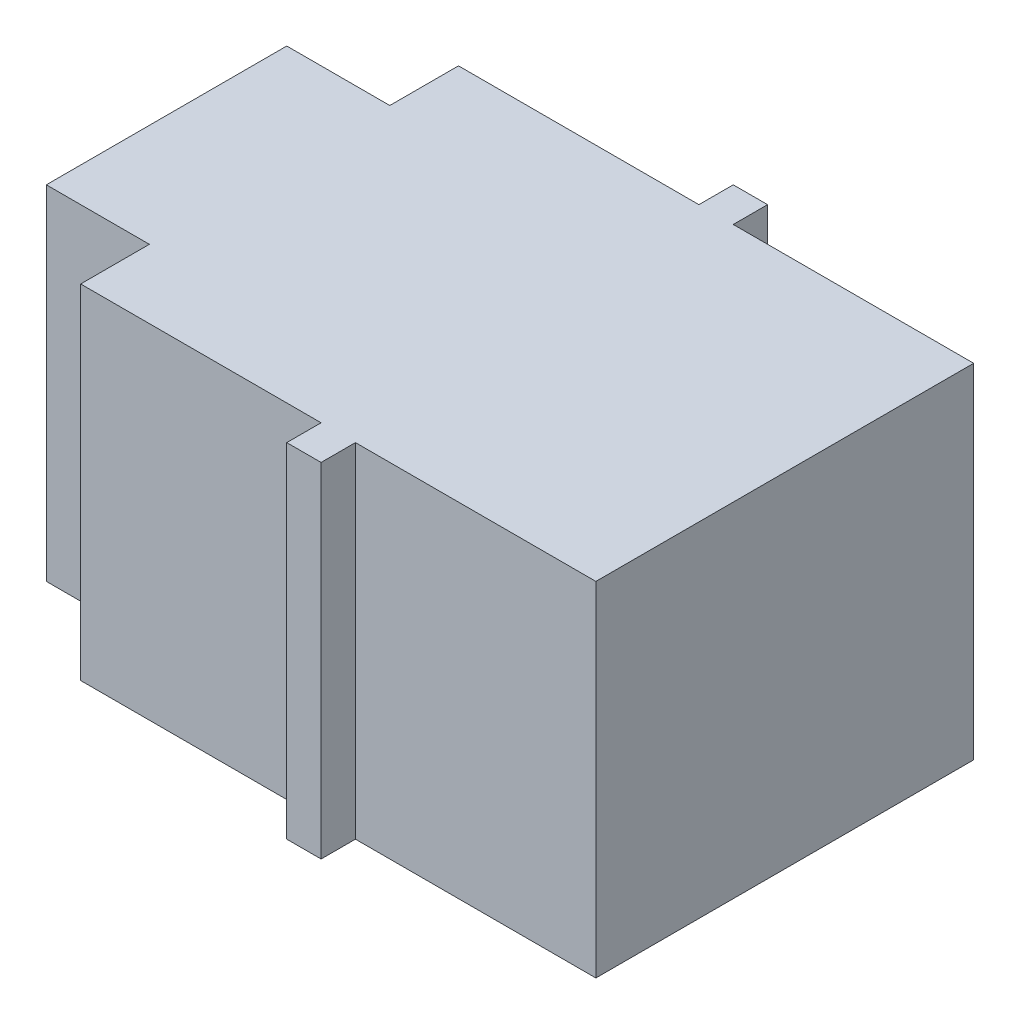
SolidWorks part; units mm, degrees
ref_plane "Front Plane" through (0, 0, 0) normal (0, 0, 1) x (1, 0, 0)
ref_plane "Top Plane" through (0, 0, 0) normal (0, 1, 0) x (1, 0, 0)
ref_plane "Right Plane" through (0, 0, 0) normal (1, 0, 0) x (0, 0, -1)
sketch "Sketch1" plane through (0, 0, 0) normal (0, 1, 0) x (1, 0, 0)
  line L0 (7.9713, 0) -> (-10.0287, 0) construction
  line L1 (-10.0287, -3.5) -> (-10.0287, 3.5)
  line L2 (-9.8287, 3.3) -> (-6.8287, 3.3)
  line L3 (-9.8287, -3.3) -> (-9.8287, 2.3) construction
  line L4 (-10.0287, -3.5) -> (-10.0287, 2.5) construction
  line L5 (-10.0287, 3.5) -> (-7.0287, 3.5)
  line L6 (-6.8287, 3.3) -> (-6.8287, 5.3)
  line L7 (-6.8287, 5.3) -> (0.1713, 5.3)
  line L8 (0.1713, 5.3) -> (0.7713, 5.3)
  line L9 (7.9713, 5.5) -> (7.9713, -5.5)
  line L10 (0.9713, -5.5) -> (7.9713, -5.5)
  line L11 (0.9713, -6.5) -> (0.9713, -5.5)
  line L12 (-0.0287, -6.5) -> (0.9713, -6.5)
  line L13 (-0.0287, -5.5) -> (-0.0287, -6.5)
  line L14 (-7.0287, -5.5) -> (-0.0287, -5.5)
  line L15 (-7.0287, -3.5) -> (-7.0287, -5.5)
  line L16 (-10.0287, -3.5) -> (-7.0287, -3.5)
  line L17 (0.7713, 5.3) -> (7.7713, 5.3)
  line L18 (7.7713, 5.3) -> (7.7713, -5.3)
  line L19 (0.7713, -5.3) -> (7.7713, -5.3)
  line L20 (0.1713, -5.3) -> (0.7713, -5.3)
  line L21 (7.7713, 4.1) -> (7.7713, -5.3) construction
  line L22 (7.9713, 4.3) -> (7.9713, -5.5) construction
  line L23 (-6.8287, -5.3) -> (0.1713, -5.3)
  line L24 (-6.8287, -3.3) -> (-6.8287, -5.3)
  line L25 (-9.8287, -3.3) -> (-6.8287, -3.3)
  line L26 (-9.8287, -3.3) -> (-9.8287, 3.3)
  line L27 (-7.0287, 3.5) -> (-7.0287, 5.5)
  line L28 (-7.0287, 5.5) -> (-0.0287, 5.5)
  line L29 (-0.0287, 5.5) -> (-0.0287, 6.5)
  line L30 (-0.0287, 6.5) -> (0.9713, 6.5)
  line L31 (0.9713, 6.5) -> (0.9713, 5.5)
  line L32 (0.9713, 5.5) -> (7.9713, 5.5)
  line L33 (0.3713, 4.9) -> (0.3713, 4.1) construction
  line L34 (0.1713, 4.9) -> (0.3713, 4.9) construction
  line L35 (0.1713, 4.1) -> (0.1713, 4.9) construction
  line L36 (0.7713, -6.3) -> (0.7713, -5.3) construction
  line L37 (0.1713, -5.3) -> (0.1713, -6.3) construction
  line L38 (0.1713, -6.3) -> (0.7713, -6.3) construction
  line L39 (0.5713, 4.3) -> (7.9713, 4.3) construction
  line L40 (0.3713, 4.1) -> (7.7713, 4.1) construction
  line L41 (-6.6287, 4.1) -> (0.1713, 4.1) construction
  line L42 (-6.8287, 4.3) -> (-0.0287, 4.3) construction
  line L43 (0.5713, 5.1) -> (0.5713, 4.3) construction
  line L44 (-0.0287, 5.1) -> (0.5713, 5.1) construction
  line L45 (-0.0287, 4.3) -> (-0.0287, 5.1) construction
  line L46 (-6.8287, 2.5) -> (-6.8287, 4.3) construction
  line L47 (-10.0287, 2.5) -> (-6.8287, 2.5) construction
  line L48 (-9.8287, 2.3) -> (-6.6287, 2.3) construction
  line L49 (-6.6287, 2.3) -> (-6.6287, 4.1) construction
  point P15 (7.9713, 0)
  point P39 (-9.8287, 0)
  point P43 (7.7713, 0)
  dimension "D9" = 0.2
extrude "Boss-Extrude1" add sketch "Sketch1" along normal blind 10
ref_plane "Plane1" through (0, 10, 0) normal (0, 1, 0) x (1, 0, 0)
ref_plane "Plane2" through (0, 0, 0) normal (0, -1, 0) x (-1, 0, 0)
sketch "Sketch6" plane through (0, 0, 0) normal (0, -1, 0) x (-1, 0, 0)
  line L1 (-7.7713, -5.3) -> (6.8287, -5.3)
  line L2 (-7.7713, -5.3) -> (-7.7713, 5.3)
  line L3 (-7.7713, 5.3) -> (6.8287, 5.3)
  line L4 (6.8287, -5.3) -> (6.8287, 5.3)
  line L5 (6.8287, 3.3) -> (9.8287, 3.3)
  line L6 (6.8287, 3.3) -> (6.8287, -3.3)
  line L7 (6.8287, -3.3) -> (9.8287, -3.3)
  line L8 (9.8287, 3.3) -> (9.8287, -3.3)
extrude "Boss-Extrude4" add sketch "Sketch6" against normal blind 0.2 contours L1 L4 L3 L2 | L8 L5 L4 L7
sketch "Sketch7" plane through (0, 10, 0) normal (0, 1, 0) x (1, 0, 0)
  line L1 (-6.8287, 5.3) -> (7.7713, 5.3)
  line L2 (-6.8287, 5.3) -> (-6.8287, -5.3)
  line L3 (-6.8287, -5.3) -> (7.7713, -5.3)
  line L4 (7.7713, 5.3) -> (7.7713, -5.3)
  line L5 (-6.8287, 3.3) -> (-9.8287, 3.3)
  line L6 (-6.8287, 3.3) -> (-6.8287, -3.3)
  line L7 (-6.8287, -3.3) -> (-9.8287, -3.3)
  line L8 (-9.8287, 3.3) -> (-9.8287, -3.3)
extrude "Boss-Extrude5" add sketch "Sketch7" against normal blind 0.2 contours L4 L1 L2 L3 | L5 L8 L7 L2
ref_plane "Plane4" through (-10.0287, 0, 0) normal (-1, 0, 0) x (0, 0, 1)
sketch "Sketch8" plane through (-10.0287, 0, 0) normal (-1, 0, 0) x (0, 0, 1)
  line L0 (0, 0) -> (0, 10)
  line L1 (-3.5, 0) -> (3.5, 0) construction
  line L2 (-3.5, 10) -> (3.5, 10) construction
  line L3 (-3.5, 5) -> (3.5, 5)
  line L4 (-3.5, 10) -> (-3.5, 0) construction
  line L5 (3.5, 10) -> (3.5, 0) construction
  line L6 (0, 8.0641) -> (0, 3.1359) construction
  line L7 (1.25, 8.0641) -> (1.25, 3.1359)
  line L8 (-1.25, 8.0641) -> (-1.25, 3.1359)
  arc A0 (1.25, 8.0641) -> (-1.25, 8.0641) centre (0, 8.0641) ccw
  arc A1 (-1.25, 3.1359) -> (1.25, 3.1359) centre (0, 3.1359) ccw
  point P14 (0, 5.6)
extrude "Cut-Extrude3" cut sketch "Sketch8" against normal blind 0.5 contours L7 A0 L0 L3 | L0 A0 L8 L3 | L8 A1 L0 L3 | L0 A1 L7 L3
